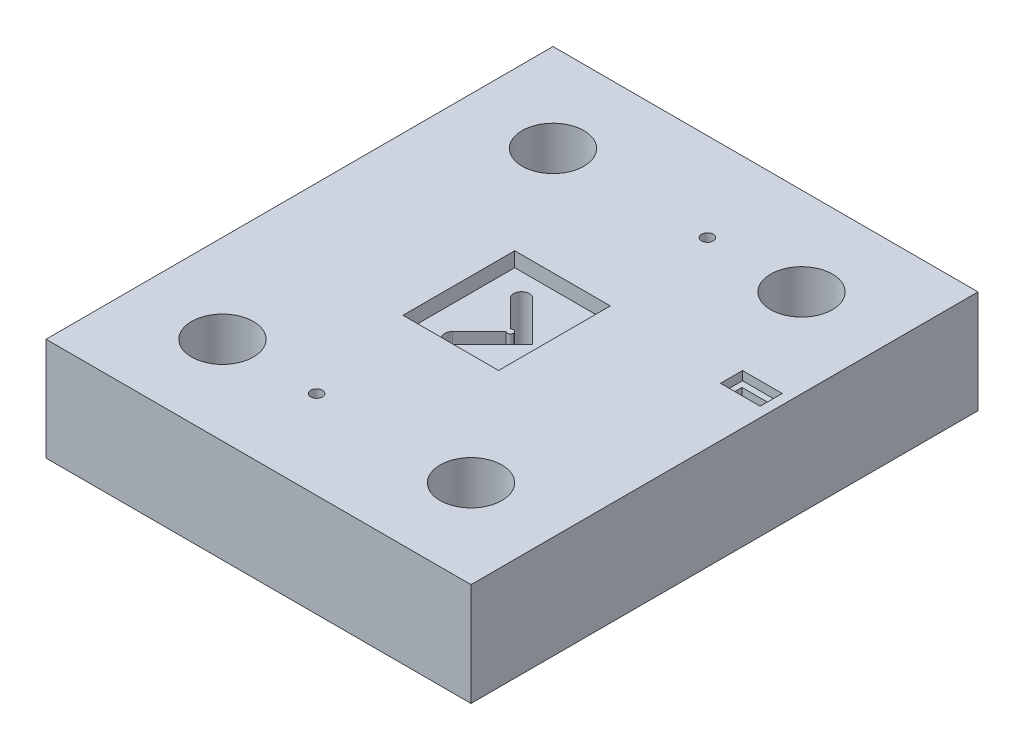
SolidWorks part; units mm, degrees
ref_plane "Front Plane" through (0, 0, 0) normal (0, 0, 1) x (1, 0, 0)
ref_plane "Top Plane" through (0, 0, 0) normal (0, 1, 0) x (1, 0, 0)
ref_plane "Right Plane" through (0, 0, 0) normal (1, 0, 0) x (0, 0, -1)
sketch "Sketch1" plane through (0, 0, 0) normal (0, 1, 0) x (1, 0, 0)
  line L1 (-72.25, -86.19) -> (72.25, -86.19)
  line L2 (-72.25, -86.19) -> (-72.25, 86.19)
  line L3 (-72.25, 86.19) -> (72.25, 86.19)
  line L4 (72.25, -86.19) -> (72.25, 86.19)
  line L5 (-72.25, -86.19) -> (72.25, 86.19) construction
  line L6 (-72.25, 86.19) -> (72.25, -86.19) construction
  point P0 (0, 0)
  dimension "D1" = 144.5
  dimension "D2" = 172.38
extrude "Boss-Extrude1" add sketch "Sketch1" along normal blind 35
sketch "Sketch2" plane through (0, 0, 0) normal (0, -1, 0) x (1, 0, 0)
  line L9 (57.25, -20.94) -> (67.25, -20.94)
  line L10 (57.25, -17.44) -> (57.25, -20.94)
  line L11 (59.25, -17.44) -> (57.25, -17.44)
  line L12 (59.25, -17.94) -> (59.25, -17.44)
  line L13 (65.25, -17.94) -> (59.25, -17.94)
  line L14 (65.25, -17.44) -> (65.25, -17.94)
  line L15 (67.25, -17.44) -> (65.25, -17.44)
  line L16 (67.25, -20.94) -> (67.25, -17.44)
  line L17 (57.25, -20.94) -> (67.25, -20.94)
  line L18 (57.25, -17.44) -> (57.25, -20.94)
  line L19 (59.25, -17.44) -> (57.25, -17.44)
  line L20 (59.25, -17.94) -> (59.25, -17.44)
  line L21 (65.25, -17.94) -> (59.25, -17.94)
  line L22 (65.25, -17.44) -> (65.25, -17.94)
  line L23 (67.25, -17.44) -> (65.25, -17.44)
  line L24 (67.25, -20.94) -> (67.25, -17.44)
  circle A0 centre (-42.25, -56.19) radius 10.5 construction
  circle A1 centre (10.25, -56.19) radius 1.99 construction
  circle A2 centre (42.25, -56.19) radius 10.5 construction
  circle A3 centre (-10.25, 56.19) radius 1.99 construction
  circle A4 centre (-42.25, 56.19) radius 10.5 construction
  circle A5 centre (42.25, 56.19) radius 10.5 construction
  circle A6 centre (-42.25, -56.19) radius 10.5
  circle A7 centre (10.25, -56.19) radius 1.99
  circle A8 centre (42.25, -56.19) radius 10.5
  circle A9 centre (-10.25, 56.19) radius 1.99
  circle A10 centre (-42.25, 56.19) radius 10.5
  circle A11 centre (42.25, 56.19) radius 10.5
  dimension "D1" = 0
extrude "Cut-Extrude1" cut sketch "Sketch2" against normal through all
sketch "Sketch3" plane through (0, 0, 0) normal (0, -1, 0) x (1, 0, 0)
  circle A0 centre (-42.25, -56.19) radius 15.25 construction
  circle A1 centre (42.25, -56.19) radius 15.25 construction
  circle A2 centre (-42.25, 56.19) radius 15.25 construction
  circle A3 centre (42.25, 56.19) radius 15.25 construction
  circle A4 centre (-42.25, -56.19) radius 15.25
  circle A5 centre (42.25, -56.19) radius 15.25
  circle A6 centre (-42.25, 56.19) radius 15.25
  circle A7 centre (42.25, 56.19) radius 15.25
extrude "Cut-Extrude2" cut sketch "Sketch3" against normal blind 20
sketch "Sketch4" plane through (0, 35, 0) normal (0, 1, 0) x (1, 0, 0)
  line L1 (-18.6217, -18.4458) -> (13.8783, -18.4458)
  line L2 (-18.6217, -18.4458) -> (-18.6217, 19.5542)
  line L3 (-18.6217, 19.5542) -> (13.8783, 19.5542)
  line L4 (13.8783, -18.4458) -> (13.8783, 19.5542)
  line L5 (55.3792, 15.5037) -> (68.8792, 15.5037) construction
  line L6 (55.3792, 15.5037) -> (55.3792, 23.0037) construction
  line L7 (55.3792, 23.0037) -> (68.8792, 23.0037) construction
  line L8 (68.8792, 15.5037) -> (68.8792, 23.0037) construction
  dimension "D1" = 13.5
  dimension "D2" = 7.5
  dimension "D3" = 32.5
  dimension "D4" = 38
extrude "Cut-Extrude3" cut sketch "Sketch4" against normal blind 5
sketch "Sketch5" plane through (0, 35, 0) normal (0, 1, 0) x (1, 0, 0)
  line L0 (55.3792, 15.5037) -> (68.8792, 15.5037) construction
  line L1 (68.8792, 15.5037) -> (68.8792, 23.0037) construction
  line L2 (55.3792, 23.0037) -> (68.8792, 23.0037) construction
  line L3 (55.3792, 15.5037) -> (55.3792, 23.0037) construction
  line L4 (55.3792, 15.5037) -> (68.8792, 15.5037)
  line L5 (68.8792, 15.5037) -> (68.8792, 23.0037)
  line L6 (55.3792, 23.0037) -> (68.8792, 23.0037)
  line L7 (55.3792, 15.5037) -> (55.3792, 23.0037)
extrude "Cut-Extrude4" cut sketch "Sketch5" against normal blind 3
sketch "Sketch6" plane through (0, 0, 0) normal (0, -1, 0) x (1, 0, 0)
  line L4 (-1.3054, -0.7635) -> (-10.4131, -9.8712)
  line L5 (-1.3054, -0.7635) -> (-10.4131, -9.8712)
  line L6 (-6.623, -13.6613) -> (7.01, -0.0283)
  line L7 (-6.623, -13.6613) -> (7.01, -0.0283)
  line L16 (7.01, -0.0283) -> (-6.623, 13.6047)
  line L17 (7.01, -0.0283) -> (-6.623, 13.6047)
  line L18 (-10.4131, 9.8146) -> (-1.3054, 0.707)
  line L19 (-10.4131, 9.8146) -> (-1.3054, 0.707)
  arc A3 (-1.3054, -0.7635) -> (-1.3054, 0.707) centre (-0.5985, -0.0283) ccw
  arc A4 (-1.3054, -0.7635) -> (-1.3054, 0.707) centre (-0.5985, -0.0283) ccw
  arc A5 (-10.4131, -9.8712) -> (-6.623, -13.6613) centre (-8.5181, -11.7663) ccw
  arc A12 (-10.4131, -9.8712) -> (-6.623, -13.6613) centre (-8.5181, -11.7663) ccw
  arc A13 (-6.623, 13.6047) -> (-10.4131, 9.8146) centre (-8.5181, 11.7097) ccw
  arc A14 (-6.623, 13.6047) -> (-10.4131, 9.8146) centre (-8.5181, 11.7097) ccw
  dimension "D1" = 0
extrude "Cut-Extrude5" cut sketch "Sketch6" against normal blind 80
